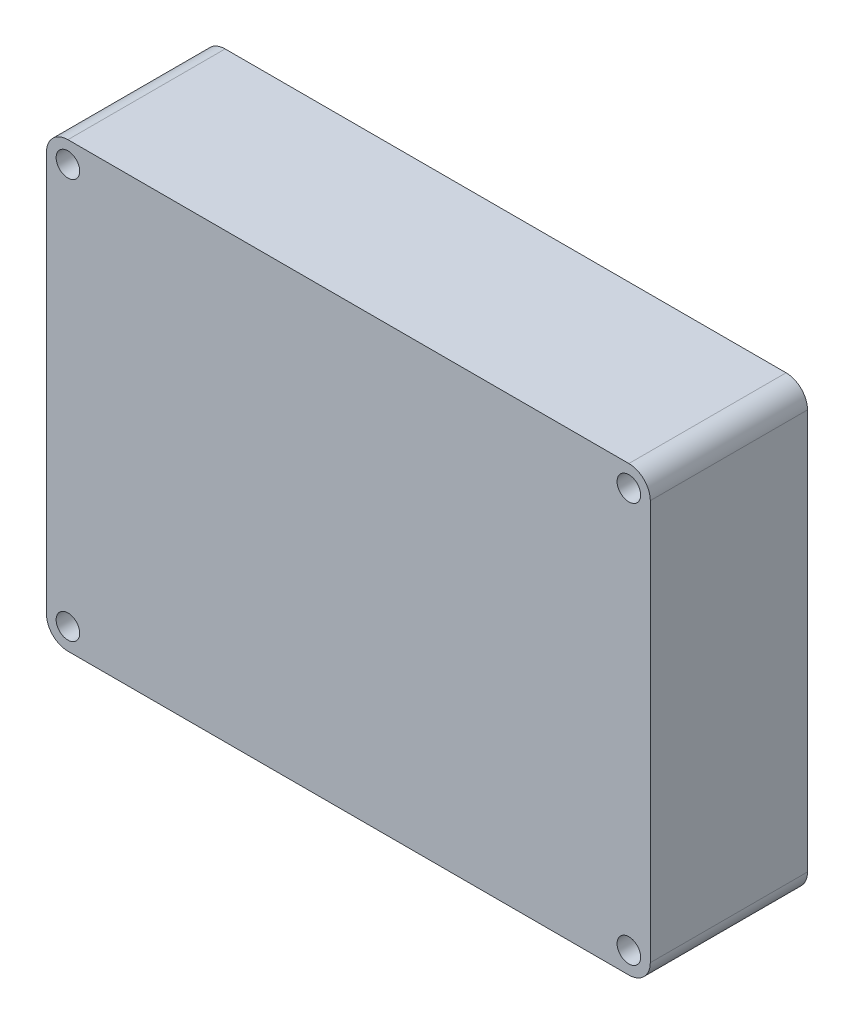
SolidWorks part; units mm, degrees
ref_plane "Alzado" through (0, 0, 0) normal (0, 0, 1) x (1, 0, 0)
ref_plane "Planta" through (0, 0, 0) normal (0, 1, 0) x (1, 0, 0)
ref_plane "Vista lateral" through (0, 0, 0) normal (1, 0, 0) x (0, 0, -1)
sketch "Croquis1" plane through (0, 0, 0) normal (0, 0, 1) x (1, 0, 0)
  line L1 (0, 0) -> (84.5, 0)
  line L2 (0, 0) -> (0, 62)
  line L3 (0, 62) -> (84.5, 62)
  line L4 (84.5, 0) -> (84.5, 62)
  circle A0 centre (3, 3) radius 1.65
  circle A1 centre (81.5, 3) radius 1.65
  circle A2 centre (81.5, 59) radius 1.65
  circle A3 centre (3, 59) radius 1.65
  point P13 (0, 0)
  point P14 (0, 0)
  point P15 (0, 0)
  point P16 (0, 0)
  dimension "D3" = 3.3
  dimension "D6" = 3
  dimension "D1" = 84.5
  dimension "D2" = 62
  dimension "D4" = 3
  dimension "D5" = 3
  dimension "D7" = 3
extrude "Saliente-Extruir1" add sketch "Croquis1" along normal blind 22
fillet "Redondeo1" radius 3 4 edges at (0, 0, 11) (84.5, 0, 11) (0, 62, 11) (84.5, 62, 11)
